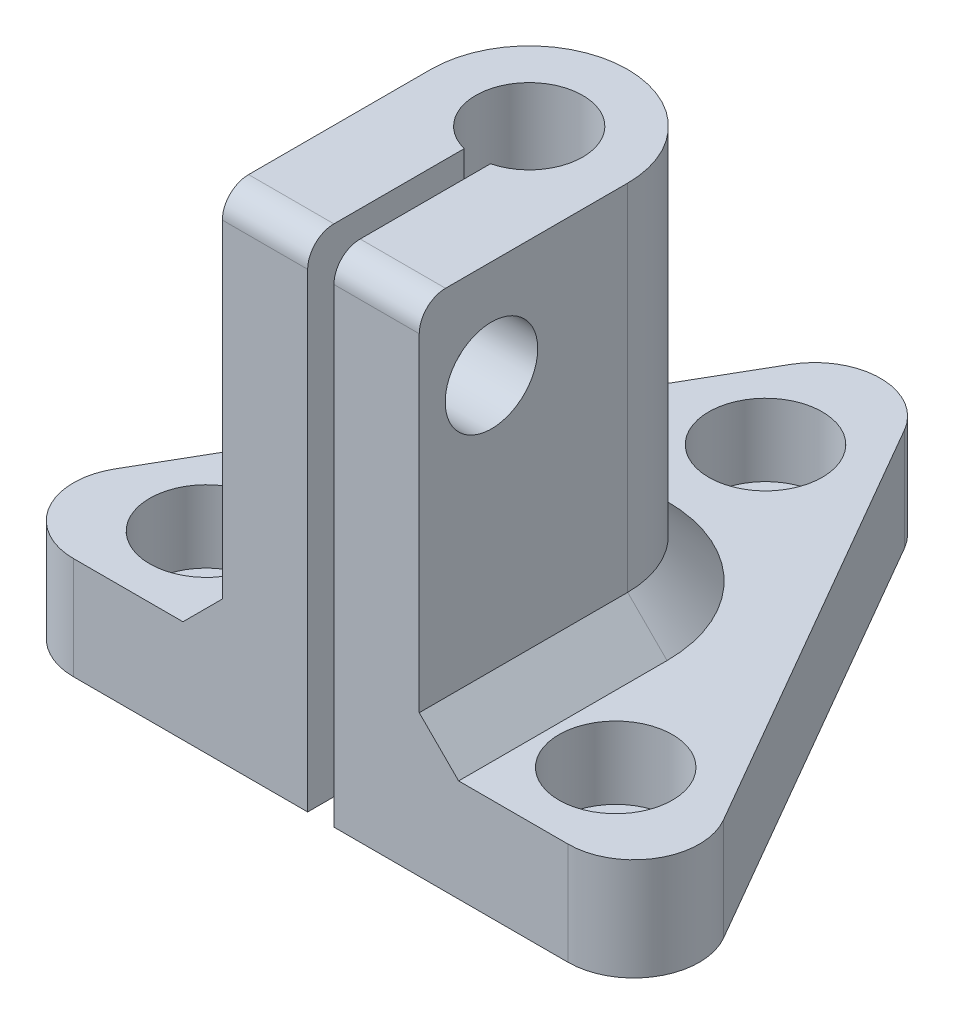
SolidWorks part; units mm, degrees
ref_plane "Plan de face" through (0, 0, 0) normal (0, 0, 1) x (1, 0, 0)
ref_plane "Plan de dessus" through (0, 0, 0) normal (0, 1, 0) x (1, 0, 0)
ref_plane "Plan de droite" through (0, 0, 0) normal (1, 0, 0) x (0, 0, -1)
sketch "Esquisse5" plane through (0, 0, 0) normal (0, 1, 0) x (1, 0, 0)
  line L0 (-27.5, -15.8771) -> (27.5, -15.8771)
  line L1 (27.5, -15.8771) -> (0, 31.7543)
  line L2 (0, 31.7543) -> (-27.5, -15.8771)
  line L3 (13.75, 7.9386) -> (-27.5, -15.8771) construction
  line L4 (-13.75, 7.9386) -> (27.5, -15.8771) construction
  circle A0 centre (0, 18) radius 2.6
  circle A1 centre (-15.5885, -9) radius 2.6
  circle A2 centre (15.5885, -9) radius 2.6
  dimension "D1" = 5.2
  dimension "D2" = 18
  dimension "D3" = 18
  dimension "D4" = 18
  dimension "D5" = 55
extrude "Boss.-Extru.2" add sketch "Esquisse5" along normal blind 7.8
sketch "Esquisse6" plane through (0, 7.8, 0) normal (0, 1, 0) x (1, 0, 0)
  circle A0 centre (0, 0) radius 7.5
  dimension "D1" = 15
extrude "Boss.-Extru.3" add sketch "Esquisse6" along normal blind 30
sketch "Esquisse13" plane through (0, 37.8, 0) normal (0, 1, 0) x (1, 0, 0)
  line L1 (-7.5, 0) -> (-7.5, -15.8771)
  line L2 (7.5, 0) -> (7.5, -15.8771)
  line L3 (-7.5, -15.8771) -> (7.5, -15.8771)
  line L4 (-27.5, -15.8771) -> (27.5, -15.8771) construction
  circle A0 centre (0, 0) radius 7.5 construction
  circle A1 centre (0, 0) radius 7.5 construction
  arc A2 (-7.5, 0) -> (7.5, 0) centre (0, 0) ccw
  point P8 (0, -15.8771)
extrude "Boss.-Extru.6" add sketch "Esquisse13" against normal up to surface (30 mm away) up to face at (0, 7.8, 7.5)
sketch "Esquisse14" plane through (0, 37.8, 0) normal (0, 1, 0) x (1, 0, 0)
  circle A0 centre (0, 0) radius 4.075
  dimension "D1" = 8.15
extrude "Enlèv. mat.-Extru.4" cut sketch "Esquisse14" against normal through all
sketch "Esquisse15" plane through (0, 37.8, 0) normal (0, 1, 0) x (1, 0, 0)
  line L1 (-1, -3.9504) -> (-1, -15.8771)
  line L2 (1, -3.9504) -> (1, -15.8771)
  line L3 (-1, -15.8771) -> (1, -15.8771)
  line L4 (-7.5, -15.8771) -> (7.5, -15.8771) construction
  line L5 (7.5, -15.8771) -> (7.5, 0) construction
  circle A0 centre (0, 0) radius 4.075 construction
  arc A1 (-1, -3.9504) -> (1, -3.9504) centre (0, 0) ccw
  dimension "D1" = 2
extrude "Enlèv. mat.-Extru.5" cut sketch "Esquisse15" against normal through all
fillet "Congé2" radius 5 3 edges at (0, 3.9, -31.7543) (-27.5, 3.9, 15.8771) (27.5, 3.9, 15.8771)
sketch "Esquisse17" plane through (7.5, 0, 0) normal (1, 0, 0) x (0, 0, -1)
  line L0 (-15.8771, 37.8) -> (0, 37.8) construction
  line L1 (-15.8771, 7.8) -> (-15.8771, 37.8) construction
  circle A0 centre (-10.3771, 30.3) radius 2.075
  dimension "D1" = 4.15
  dimension "D2" = 7.5
  dimension "D3" = 5.5
extrude "Enlèv. mat.-Extru.6" cut sketch "Esquisse17" against normal through all
sketch "Esquisse18" plane through (-7.5, 0, 0) normal (-1, 0, 0) x (0, 0, 1)
  line L0 (0, 37.8) -> (15.8771, 37.8) construction
  line L1 (12.4123, 33.825) -> (8.342, 33.825)
  line L2 (8.342, 33.825) -> (6.3068, 30.3)
  line L3 (6.3068, 30.3) -> (8.342, 26.775)
  line L4 (8.342, 26.775) -> (12.4123, 26.775)
  line L5 (12.4123, 26.775) -> (14.4475, 30.3)
  line L6 (14.4475, 30.3) -> (12.4123, 33.825)
  circle A0 centre (10.3771, 30.3) radius 3.525 construction
  dimension "D1" = 7.05
extrude "Enlèv. mat.-Extru.7" cut sketch "Esquisse18" against normal blind 3.25
chamfer "Chanfrein1" distance 3 angle 45 3 edges at (0, 7.8, -7.5) (7.5, 7.8, 7.9386) (-7.5, 7.8, 7.9386)
sketch "Esquisse20" plane through (7.5, 0, 0) normal (1, 0, 0) x (0, 0, -1)
  circle A0 centre (-10.3771, 30.3) radius 3.525
  dimension "D1" = 7.05
extrude "Enlèv. mat.-Extru.9" cut sketch "Esquisse20" against normal blind 4.97
fillet "Congé3" radius 2 2 edges at (4.25, 37.8, 15.8771) (-4.25, 37.8, 15.8771)
sketch "Esquisse19" plane through (0, 7.8, 0) normal (0, 1, 0) x (1, 0, 0)
  circle A0 centre (0, 18) radius 4.325
  circle A1 centre (-15.5885, -9) radius 4.325
  circle A2 centre (15.5885, -9) radius 4.325
  dimension "D1" = 8.65
extrude "Enlèv. mat.-Extru.8" cut sketch "Esquisse19" against normal blind 5.5
sketch "Esquisse21" plane through (2.53, 0, 0) normal (1, 0, 0) x (0, 0, -1)
  line L0 (-11.3363, 32.14) -> (-10.3771, 32.64)
  line L1 (-10.3771, 32.64) -> (-9.418, 32.14)
  line L2 (-9.418, 32.14) -> (-11.3363, 32.14)
  line L3 (-13.8771, 37.8) -> (0, 37.8) construction
  circle A0 centre (-10.3771, 30.3) radius 2.075 construction
  dimension "D1" = 0.5
extrude "Enlèv. mat.-Extru.10" cut sketch "Esquisse21" against normal through all
